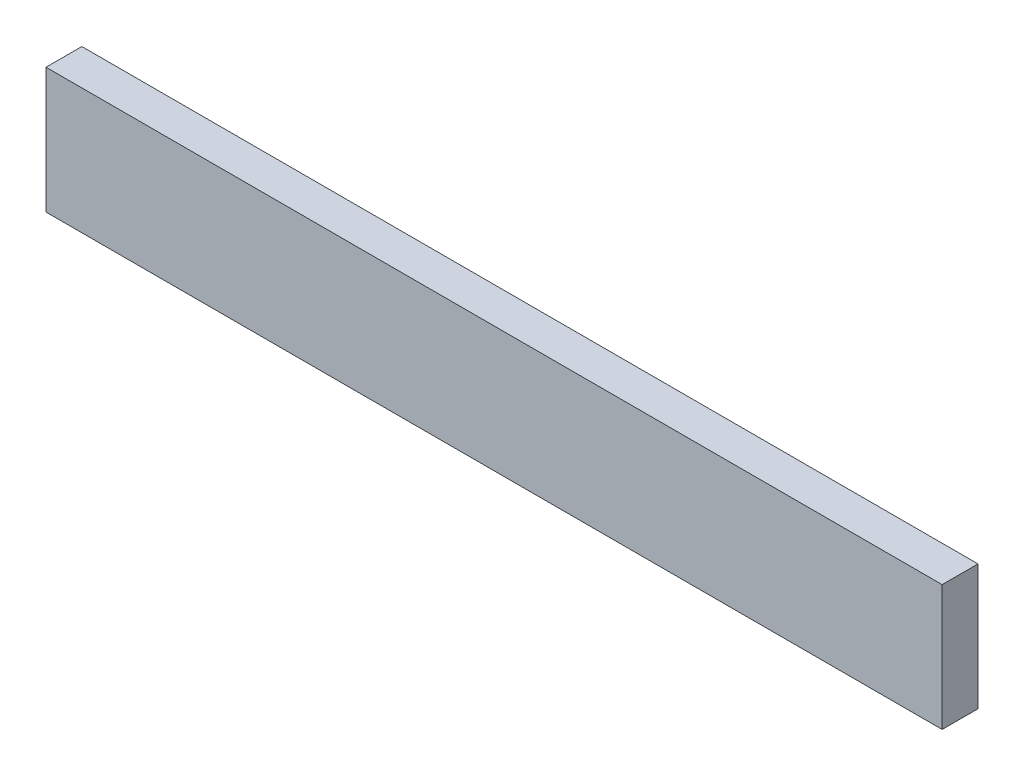
SolidWorks part; units mm, degrees
ref_plane "前视基准面" through (0, 0, 0) normal (0, 0, 1) x (1, 0, 0)
ref_plane "上视基准面" through (0, 0, 0) normal (0, 1, 0) x (1, 0, 0)
ref_plane "右视基准面" through (0, 0, 0) normal (1, 0, 0) x (0, 0, -1)
other "Configuration Table"
sketch "草图1" plane through (0, 0, 0) normal (0, 0, 1) x (1, 0, 0)
  line L1 (-250, -35) -> (250, -35)
  line L2 (-250, -35) -> (-250, 35)
  line L3 (-250, 35) -> (250, 35)
  line L4 (250, -35) -> (250, 35)
  line L5 (-250, -35) -> (250, 35) construction
  line L6 (-250, 35) -> (250, -35) construction
  point P0 (0, 0)
extrude "凸台-拉伸1" add sketch "草图1" along normal blind 20
